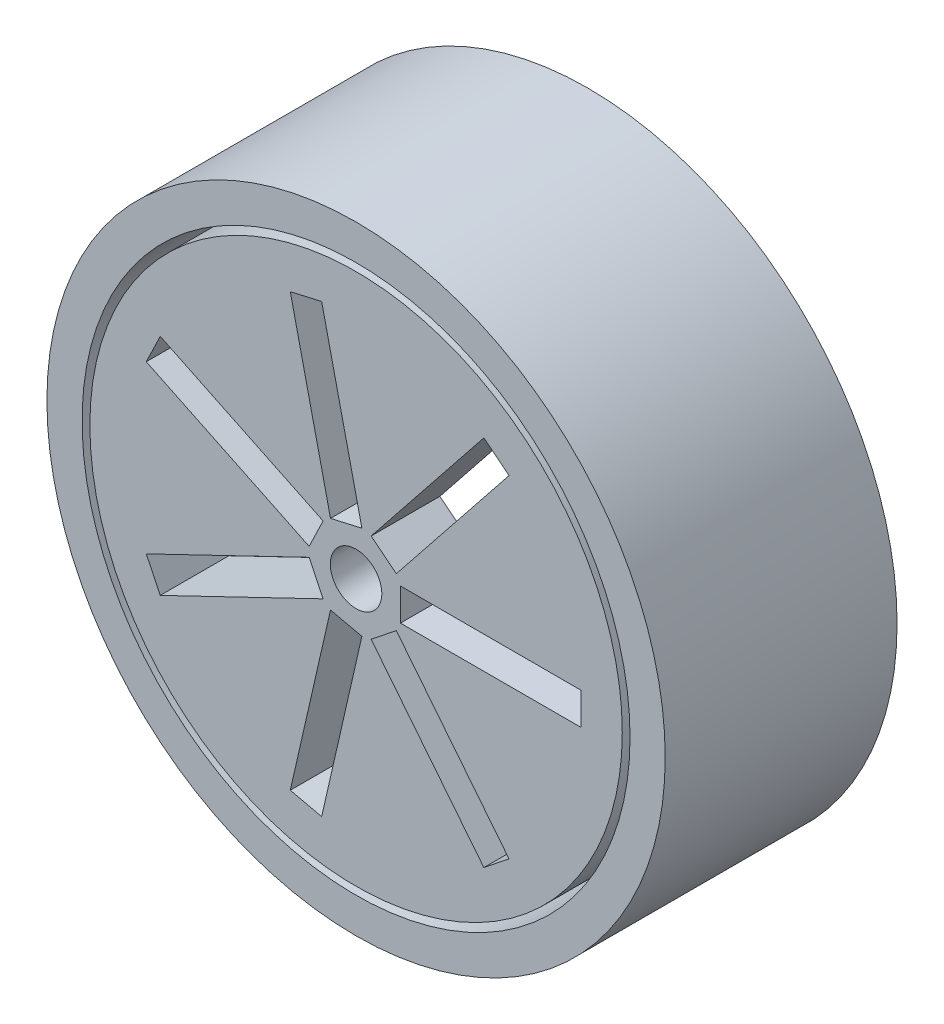
SolidWorks part; units mm, degrees
ref_plane "Plan de face" through (0, 0, 0) normal (0, 0, 1) x (1, 0, 0)
ref_plane "Plan de dessus" through (0, 0, 0) normal (0, 1, 0) x (1, 0, 0)
ref_plane "Plan de droite" through (0, 0, 0) normal (1, 0, 0) x (0, 0, -1)
sketch "Esquisse1" plane through (0, 0, 0) normal (0, 0, 1) x (1, 0, 0)
  line L0 (-31, 0) -> (31, 0) construction
  line L1 (0, 31) -> (0, -31) construction
  line L2 (1.7553, -5.2059) -> (17.8092, -19.3273) construction
  line L3 (5.1646, -1.8735) -> (26.2145, -1.8735)
  line L4 (5.1646, -1.8735) -> (5.1646, 1.8735)
  line L5 (5.1646, 1.8735) -> (26.2145, 1.8735)
  line L6 (26.2145, -1.8735) -> (26.2145, 1.8735)
  line L7 (5.1646, -1.8735) -> (26.2145, 1.8735) construction
  line L8 (5.1646, 1.8735) -> (26.2145, -1.8735) construction
  line L9 (4.6848, -2.8697) -> (14.8798, -21.6634) construction
  line L10 (1.7553, -5.2059) -> (4.6848, -2.8697)
  line L11 (1.7553, -5.2059) -> (14.8798, -21.6634)
  line L12 (14.8798, -21.6634) -> (17.8092, -19.3273)
  line L13 (4.6848, -2.8697) -> (17.8092, -19.3273)
  line L14 (-2.9757, -4.6182) -> (-4.0068, -25.9742) construction
  line L15 (0.6773, -5.452) -> (-7.6598, -25.1404) construction
  line L16 (-2.9757, -4.6182) -> (0.6773, -5.452)
  line L17 (-2.9757, -4.6182) -> (-7.6598, -25.1404)
  line L18 (-7.6598, -25.1404) -> (-4.0068, -25.9742)
  line L19 (0.6773, -5.452) -> (-4.0068, -25.9742)
  line L20 (-5.466, -0.5529) -> (-22.8056, -13.062) construction
  line L21 (-3.8403, -3.9287) -> (-24.4314, -9.6861) construction
  line L22 (-5.466, -0.5529) -> (-3.8403, -3.9287)
  line L23 (-5.466, -0.5529) -> (-24.4314, -9.6861)
  line L24 (-24.4314, -9.6861) -> (-22.8056, -13.062)
  line L25 (-3.8403, -3.9287) -> (-22.8056, -13.062)
  line L26 (-3.8403, 3.9287) -> (-24.4314, 9.6861) construction
  line L27 (-5.466, 0.5529) -> (-22.8056, 13.062) construction
  line L28 (-3.8403, 3.9287) -> (-5.466, 0.5529)
  line L29 (-3.8403, 3.9287) -> (-22.8056, 13.062)
  line L30 (-22.8056, 13.062) -> (-24.4314, 9.6861)
  line L31 (-5.466, 0.5529) -> (-24.4314, 9.6861)
  line L32 (0.6773, 5.452) -> (-7.6598, 25.1404) construction
  line L33 (-2.9757, 4.6182) -> (-4.0068, 25.9742) construction
  line L34 (0.6773, 5.452) -> (-2.9757, 4.6182)
  line L35 (0.6773, 5.452) -> (-4.0068, 25.9742)
  line L36 (-4.0068, 25.9742) -> (-7.6598, 25.1404)
  line L37 (-2.9757, 4.6182) -> (-7.6598, 25.1404)
  line L38 (4.6848, 2.8697) -> (14.8798, 21.6634) construction
  line L39 (1.7553, 5.2059) -> (17.8092, 19.3273) construction
  line L40 (4.6848, 2.8697) -> (1.7553, 5.2059)
  line L41 (4.6848, 2.8697) -> (17.8092, 19.3273)
  line L42 (17.8092, 19.3273) -> (14.8798, 21.6634)
  line L43 (1.7553, 5.2059) -> (14.8798, 21.6634)
  circle A0 centre (0, 0) radius 31
  point P7 (15.6896, 0)
  point P15 (9.7823, -12.2666)
  point P20 (-3.4913, -15.2962)
  point P25 (-14.1358, -6.8074)
  point P30 (-14.1358, 6.8074)
  point P35 (-3.4913, 15.2962)
  point P40 (9.7823, 12.2666)
  point P45 (0, 0)
  dimension "D1" = 7
extrude "Boss.-Extru.1" add sketch "Esquisse1" along normal blind 27
sketch "Esquisse2" plane through (0, 0, 27) normal (0, 0, 1) x (1, 0, 0)
  circle A0 centre (0, 0) radius 3
extrude "Enlèv. mat.-Extru.1" cut sketch "Esquisse2" against normal blind 27
sketch "Esquisse3" plane through (0, 0, 27) normal (0, 0, 1) x (1, 0, 0)
  circle A0 centre (0, 0) radius 31.9049
  circle A1 centre (0, 0) radius 36
extrude "Boss.-Extru.2" add sketch "Esquisse3" against normal through all
sketch "Esquisse4" plane through (0, 0, 0) normal (0, 0, -1) x (-1, 0, 0)
  circle A0 centre (0, 0) radius 3
  circle A1 centre (0, 0) radius 26.2814
extrude "Enlèv. mat.-Extru.2" cut sketch "Esquisse4" against normal blind 19
